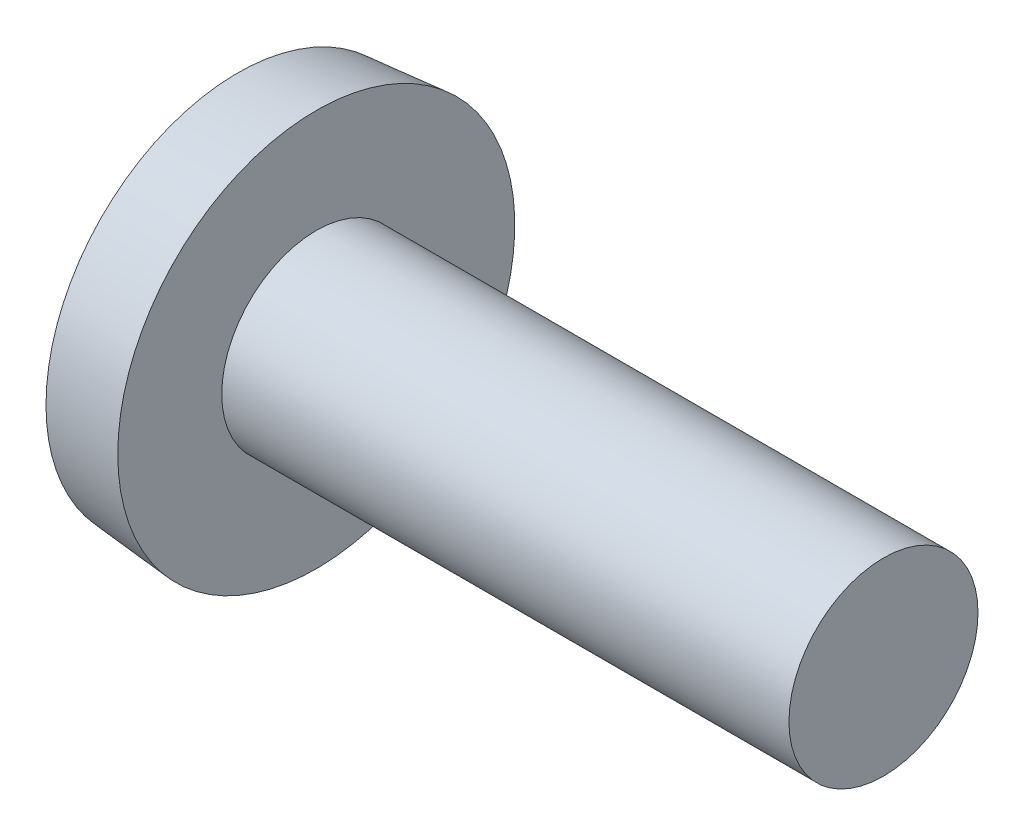
SolidWorks part; units mm, degrees
ref_plane "Plane1" through (0, 0, 0) normal (0, 0, 1) x (1, 0, 0)
ref_plane "Plane2" through (0, 0, 0) normal (0, 1, 0) x (1, 0, 0)
ref_plane "Plane3" through (0, 0, 0) normal (1, 0, 0) x (0, 0, -1)
sketch "BodySke" plane through (0, 0, 0) normal (0, 0, 1) x (1, 0, 0)
  line L0 (4.191, 3.175) -> (4.191, 6.6675)
  line L1 (4.191, 6.6675) -> (1.5494, 6.4364)
  line L2 (-25.4, 0) -> (127, 0) construction
  line L3 (4.191, -6.6675) -> (1.5494, -6.4364) construction
  line L4 (4.191, 3.175) -> (23.241, 3.175)
  line L5 (23.241, 3.175) -> (23.241, 0)
  line L6 (23.241, 0) -> (0, 0)
  line L7 (4.191, -3.175) -> (23.241, -3.175) construction
  line L8 (5.461, 6.35) -> (5.461, -3.175) construction
  line L9 (4.191, 6.35) -> (4.191, -3.175) construction
  arc A0 (0, 0) -> (1.5494, 6.4364) centre (14.1435, 0) cw
  dimension "Head_ang" = 85
  dimension "Oval_ht" = 1.5494
  dimension "Head_ht" = 4.191
  dimension "Diameter" = 6.35
  dimension "Length" = 19.05
  dimension "Head_dia" = 13.335
  dimension "Advance" = 1.27
  dimension "Thread_nom" = 19.05
revolve "Base-Revolve" add sketch "BodySke" angle 360 about L2
cosmetic thread "ThreadCosmetic" parameters "Thread_length"=17.78, "Thread_minor"=4.8387
sketch "Sketch2" plane through (0, 0, 0) normal (1, 0, 0) x (0, 0, -1)
  line L0 (6.6675, -0.9525) -> (6.6675, 0.9525)
  line L1 (6.6675, 0.9525) -> (-6.6675, 0.9525)
  line L2 (-6.6675, 0.9525) -> (-6.6675, -0.9525)
  line L3 (-6.6675, -0.9525) -> (6.6675, -0.9525)
  dimension "D1" = 13.335
  dimension "D2" = 6.6675
  dimension "D3" = 0.9525
  dimension "Slot_width" = 1.905
extrude "Slot" [suppressed] cut sketch "Sketch2" along normal blind 2.667
sketch "Sketch3" plane through (0, 0, 0) normal (1, 0, 0) x (0, 0, -1)
  line L0 (-0.7493, 4.1783) -> (0.7493, 4.1783)
  line L1 (0.7493, 4.1783) -> (0.7493, -4.1783)
  line L2 (0.7493, -4.1783) -> (-0.7493, -4.1783)
  line L3 (-0.7493, -4.1783) -> (-0.7493, 4.1783)
  dimension "Cross_width" = 1.4986
  dimension "D1" = 0.7493
  dimension "Cross_dia" = 8.3566
  dimension "D2" = 4.1783
ref_plane "Plane4" through (4.7498, 0, 0) normal (1, 0, 0) x (0, 0, -1)
sketch "Sketch4" plane through (4.7498, 0, 0) normal (1, 0, 0) x (0, 0, -1)
  line L0 (-0.3746, 0.3746) -> (0.3746, 0.3746)
  line L1 (0.3746, 0.3746) -> (0.3747, -0.3746)
  line L2 (0.3747, -0.3746) -> (-0.3746, -0.3747)
  line L3 (-0.3746, -0.3747) -> (-0.3746, 0.3746)
  dimension "D1" = 0.7493
  dimension "D2" = 0.3746
  dimension "D3" = 0.7493
  dimension "D4" = 0.3746
loft "Cross" cut profiles "Sketch3", "Sketch4"
pattern_circular "CirPattern1" count 2 every 90 about axis through (0, 0, 0) along (1, 0, 0) of "Cross"
sketch "ThdSchSke" plane through (0, 0, 0) normal (0, 0, 1) x (1, 0, 0)
  line L0 (5.461, -2.4193) -> (4.9319, -3.175)
  line L1 (5.461, -2.4193) -> (5.9901, -3.175)
  line L2 (5.9901, -3.175) -> (5.9901, -3.9687)
  line L3 (-3.175, 0) -> (5.1513, 0) construction
  line L5 (5.9901, -3.9687) -> (4.9319, -3.9688)
  line L6 (4.9319, -3.9688) -> (4.9319, -3.175)
  dimension "Diameter" = 6.35
  dimension "SideAngle" = 55
  dimension "VeeAngle" = 70
  dimension "Thread_minor" = 4.8387
  dimension "Overcut" = 7.9375
  dimension "Start" = 5.461
revolve "ThreadSchematic" [suppressed] cut sketch "ThdSchSke" angle 360 about L3
pattern_linear "ThdSchPat" [suppressed]
equation "\"D1@Sketch3\" = \"Cross_width@Sketch3\" / 2"
equation "\"D2@Sketch3\" = \"Cross_dia@Sketch3\" / 2"
equation "\"D1@Sketch4\" = \"Cross_width@Sketch3\"*.5"
equation "\"D2@Sketch4\" = \"D1@Sketch4\" / 2"
equation "\"D3@Sketch4\" = \"D1@Sketch4\""
equation "\"D4@Sketch4\" = \"D2@Sketch4\""
equation "\"D1@Sketch2\" = \"Head_dia@BodySke\""
equation "\"D2@Sketch2\" = \"D1@Sketch2\" / 2"
equation "\"D3@Sketch2\" = \"Slot_width@Sketch2\" / 2"
equation "\"Thread_length@ThreadCosmetic\" = ((sgn( (\"Length@BodySke\" - \"Advance@BodySke\" ) - \"Thread_nom@BodySke\" )-1)*( (\"Length@BodySke\" - \"Advance@BodySke\" ) - \"Thread_nom@BodySke\" ))/-2+ \"Thread_nom@BodySke\""
equation "\"Thread_minor@ThdSchSke\" = \"Thread_minor@ThreadCosmetic\""
equation "\"Diameter@ThdSchSke\" = \"Diameter@BodySke\""
equation "\"Overcut@ThdSchSke\" = \"Diameter@BodySke\" * 1.25"
equation "\"Start@ThdSchSke\" = \"Head_ht@BodySke\" + \"Length@BodySke\" - \"Thread_length@ThreadCosmetic\"  '---Non-countersunk---"
equation "\"Num_threads@ThdSchPat\" = int( \"Thread_length@ThreadCosmetic\" / \"Advance@BodySke\" + 0.999 )  + 1"
equation "\"Advance@ThdSchPat\" = \"Thread_length@ThreadCosmetic\" /  (\"Num_threads@ThdSchPat\" - 1) 'relax it"
